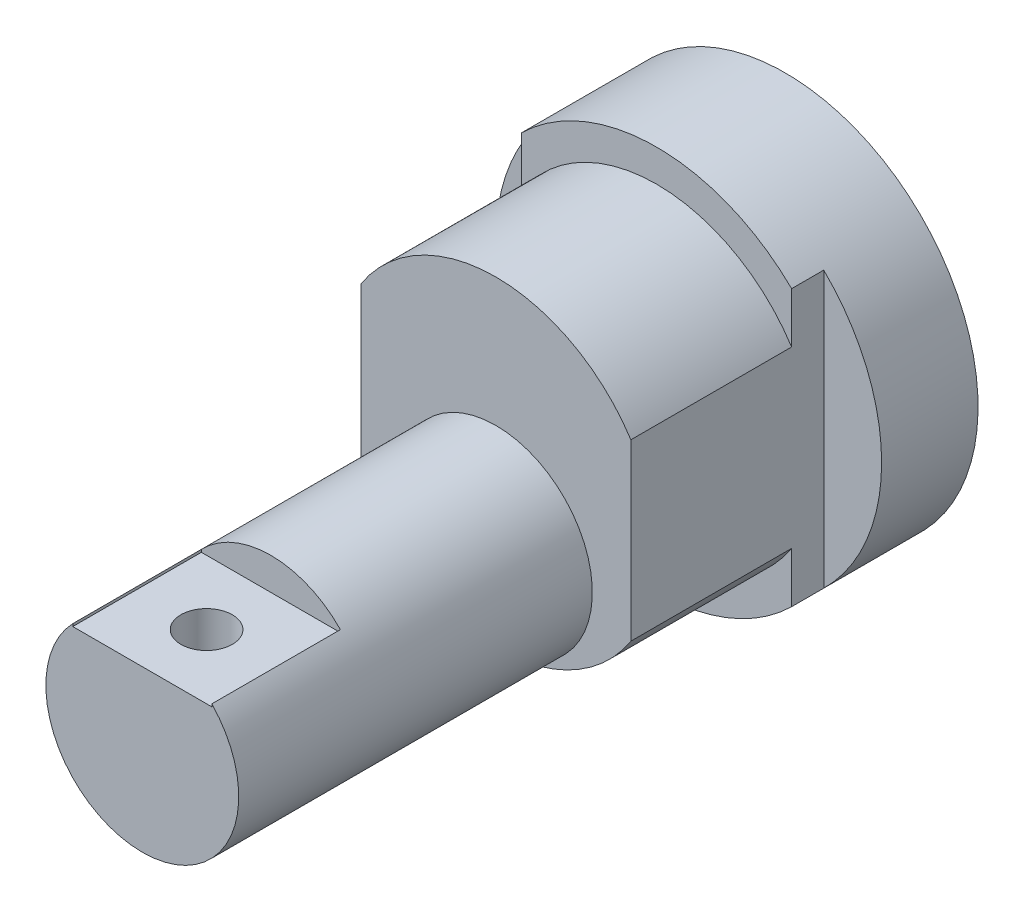
SolidWorks part; units mm, degrees
ref_plane "Ön Düzlem" through (0, 0, 0) normal (0, 0, 1) x (1, 0, 0)
ref_plane "Üst Düzlem" through (0, 0, 0) normal (0, 1, 0) x (1, 0, 0)
ref_plane "Sağ Düzlem" through (0, 0, 0) normal (1, 0, 0) x (0, 0, -1)
sketch "Çizim1" plane through (0, 0, 0) normal (0, 0, 1) x (1, 0, 0)
  circle A0 centre (0, 0) radius 15
  dimension "D1" = 30
extrude "Yükseklik-Ekstrüzyon1" add sketch "Çizim1" against normal blind 55
sketch "Çizim2" plane through (0, 0, -55) normal (0, 0, -1) x (-1, 0, 0)
  circle A1 centre (0, 0) radius 15 construction
  circle A2 centre (0, 10) radius 25
  point P2 (0, -15)
  dimension "D1" = 10
  dimension "D2" = 50
extrude "Yükseklik-Ekstrüzyon2" add sketch "Çizim2" along normal blind 25
sketch "Çizim3" plane through (0, 0, -80) normal (0, 0, -1) x (-1, 0, 0)
  circle A1 centre (0, 10) radius 30
  point P0 (0, -15)
  point P5 (0, 0)
  dimension "D1" = 60
  dimension "D2" = 25
extrude "Yükseklik-Ekstrüzyon3" add sketch "Çizim3" along normal blind 20
ref_plane "Düzlem1" through (0, 10, 0) normal (0, 1, 0) x (1, 0, 0)
sketch "Çizim4" plane through (0, 10, 0) normal (0, 1, 0) x (1, 0, 0)
  line L0 (-15, 0) -> (15, 0) construction
  line L1 (-10.8113, 20) -> (10.8113, 20)
  line L2 (-10.8113, 20) -> (-10.8113, 0)
  line L3 (-10.8113, 0) -> (10.8113, 0)
  line L4 (10.8113, 20) -> (10.8113, 0)
  circle A0 centre (0, 10) radius 4
  point P0 (0, 10)
  dimension "D1" = 8
  dimension "D2" = 10
  dimension "D3" = 20
extrude "Kes-Ekstrüzyon1" cut sketch "Çizim4" along normal blind 20 contours L4 L3 L2 L1
sketch "Çizim6" plane through (0, 10, 0) normal (0, 1, 0) x (1, 0, 0)
  circle A0 centre (0, 10) radius 4 construction
  circle A1 centre (0, 10) radius 4
extrude "Kes-Ekstrüzyon2" cut sketch "Çizim6" against normal blind 30
ref_plane "Düzlem2" through (21, 0, 0) normal (1, 0, 0) x (0, 0, -1)
sketch "Çizim7" plane through (21, 0, 0) normal (1, 0, 0) x (0, 0, -1)
  line L0 (55, -7.517) -> (80, -7.517)
  line L1 (55, 35) -> (55, -15) construction
  line L2 (80, 35) -> (80, -15) construction
  line L3 (80, -7.517) -> (80, -20)
  line L4 (80, -20) -> (85, -20)
  line L5 (80, -20) -> (100, -20) construction
  line L6 (85, -20) -> (85, 40)
  line L7 (100, 40) -> (80, 40) construction
  line L8 (85, 40) -> (80, 40)
  line L9 (80, 40) -> (80, 25)
  line L10 (80, 25) -> (55, 25)
  line L11 (55, 25) -> (55, -7.517)
  line L12 (80, 40) -> (80, -20) construction
  point P7 (0, 0)
  point P20 (80, -20)
  dimension "D1" = 30
  dimension "D2" = 15
extrude "Kes-Ekstrüzyon3" cut sketch "Çizim7" along normal blind 30
mirror "Aynalama1" about plane through (0, 0, 0) normal (1, 0, 0) of "Kes-Ekstrüzyon3"
